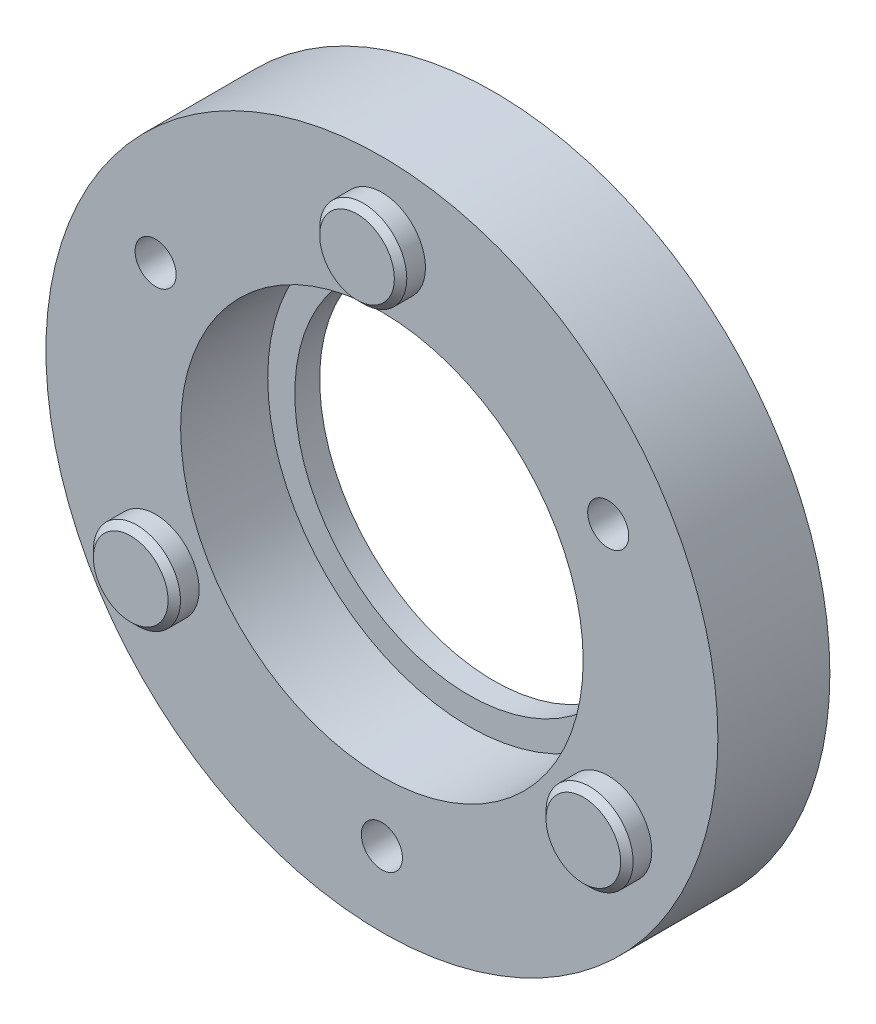
SolidWorks part; units mm, degrees
ref_plane "Спереди" through (0, 0, 0) normal (0, 0, 1) x (1, 0, 0)
ref_plane "Сверху" through (0, 0, 0) normal (0, 1, 0) x (1, 0, 0)
ref_plane "Справа" through (0, 0, 0) normal (1, 0, 0) x (0, 0, -1)
sketch "Эскиз1" plane through (0, 0, 0) normal (0, 0, 1) x (1, 0, 0)
  circle A0 centre (0, 0) radius 27
  dimension "D1" = 54
extrude "тело" add sketch "Эскиз1" along normal blind 9
sketch "Эскиз2" plane through (0, 0, 9) normal (0, 0, 1) x (1, 0, 0)
  circle A0 centre (0, 0) radius 16.175
  dimension "D1" = 32.35
extrude "углубление подшипника" cut sketch "Эскиз2" against normal blind 7
sketch "Эскиз3" plane through (0, 0, 2) normal (0, 0, 1) x (1, 0, 0)
  circle A0 centre (0, 0) radius 14
  dimension "D1" = 28
extrude "сквозное отверстие" cut sketch "Эскиз3" against normal through all
sketch "Эскиз4" plane through (0, 0, 9) normal (0, 0, 1) x (1, 0, 0)
  line L0 (-18.1865, 10.5) -> (18.1865, 10.5) construction
  line L1 (-18.1865, 10.5) -> (0, 0) construction
  line L2 (0, 0) -> (18.1865, 10.5) construction
  circle A0 centre (0, 0) radius 21 construction
  circle A1 centre (-18.1865, 10.5) radius 1.65
  circle A2 centre (18.1865, 10.5) radius 1.65
  circle A3 centre (0, -21) radius 1.65
  dimension "D1" = 42
  dimension "D2" = 3.3
  dimension "D3" = 120
extrude "отверстия для болтов" cut sketch "Эскиз4" against normal through all
sketch "Эскиз6" plane through (0, 0, 0) normal (0, 0, -1) x (-1, 0, 0)
  line L0 (0, 0) -> (0, 21) construction
  line L1 (0, 0) -> (18.1865, -10.5) construction
  line L2 (0, 0) -> (-18.1865, -10.5) construction
  circle A0 centre (0, 0) radius 21 construction
  circle A1 centre (0, 21) radius 3.65
  circle A2 centre (-18.1865, -10.5) radius 3.65
  circle A3 centre (18.1865, -10.5) radius 3.65
  dimension "D1" = 42
  dimension "D4" = 7.3
  dimension "D2" = 120
  dimension "D3" = 120
extrude "отверстия под шипы" cut sketch "Эскиз6" against normal blind 3
sketch "Эскиз7" plane through (0, 0, 9) normal (0, 0, 1) x (1, 0, 0)
  line L0 (0, 0) -> (0, 21) construction
  line L1 (0, 0) -> (-18.1865, -10.5) construction
  line L2 (0, 0) -> (18.1865, -10.5) construction
  circle A0 centre (0, 0) radius 21 construction
  circle A1 centre (0, 21) radius 3.5
  circle A2 centre (-18.1865, -10.5) radius 3.5
  circle A3 centre (18.1865, -10.5) radius 3.5
  dimension "D1" = 42
  dimension "D2" = 7
  dimension "D3" = 120
  dimension "D4" = 120
extrude "шипы" add sketch "Эскиз7" along normal blind 2
chamfer "Фаска1" distance 0.5 angle 45 3 edges at (-14.6865, -10.5, 11) (21.6865, -10.5, 11) (3.5, 21, 11)
